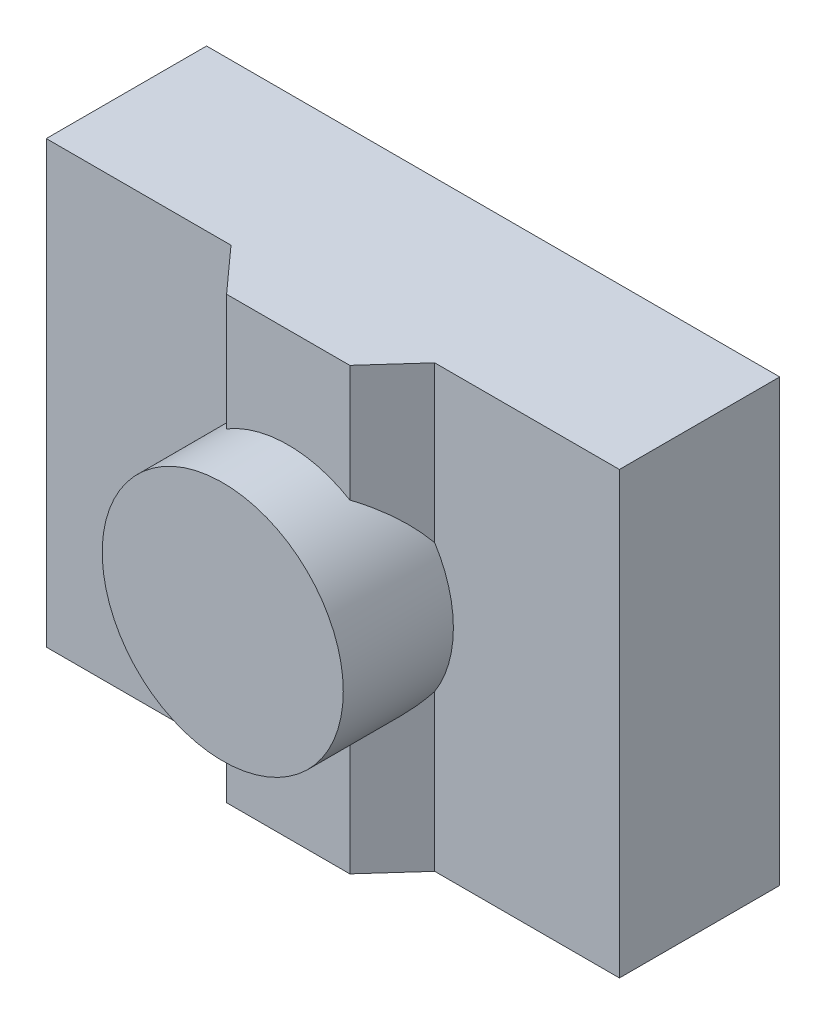
SolidWorks part; units mm, degrees
ref_plane "Front Plane" through (0, 0, 0) normal (0, 0, 1) x (1, 0, 0)
ref_plane "Top Plane" through (0, 0, 0) normal (0, 1, 0) x (1, 0, 0)
ref_plane "Right Plane" through (0, 0, 0) normal (1, 0, 0) x (0, 0, -1)
sketch "Sketch1" plane through (0, 0, 0) normal (0, 1, 0) x (1, 0, 0)
  line L0 (0, 36.9812) -> (0, 0)
  line L1 (0, 0) -> (42.6154, 0)
  line L2 (42.6154, 0) -> (51.8977, -10.3009)
  line L3 (51.8977, -10.3009) -> (80.325, -10.3009)
  line L4 (66.1114, -10.3009) -> (66.1114, 59.317) construction
  line L5 (89.6074, 0) -> (80.325, -10.3009)
  line L6 (132.2228, 0) -> (89.6074, 0)
  line L7 (132.2228, 36.9812) -> (132.2228, 0)
  line L8 (0, 36.9812) -> (132.2228, 36.9812)
extrude "Extrude1" add sketch "Sketch1" against normal blind 101.6
ref_plane "Plane1" through (0, 0, 25.4) normal (0, 0, 1) x (1, 0, 0)
sketch "Sketch2" plane through (0, 0, 25.4) normal (0, 0, 1) x (1, 0, 0)
  line L0 (51.8977, -50.8) -> (80.325, -50.8) construction
  line L1 (51.8977, -101.6) -> (51.8977, 0) construction
  line L2 (80.325, -101.6) -> (80.325, 0) construction
  circle A0 centre (66.1114, -50.8) radius 27.8057
extrude "Extrude2" add sketch "Sketch2" against normal up to body
sketch "Sketch3" plane through (0, 0, 25.4) normal (0, 0, 1) x (1, 0, 0)
  circle A0 centre (66.1114, -50.8) radius 23.594
